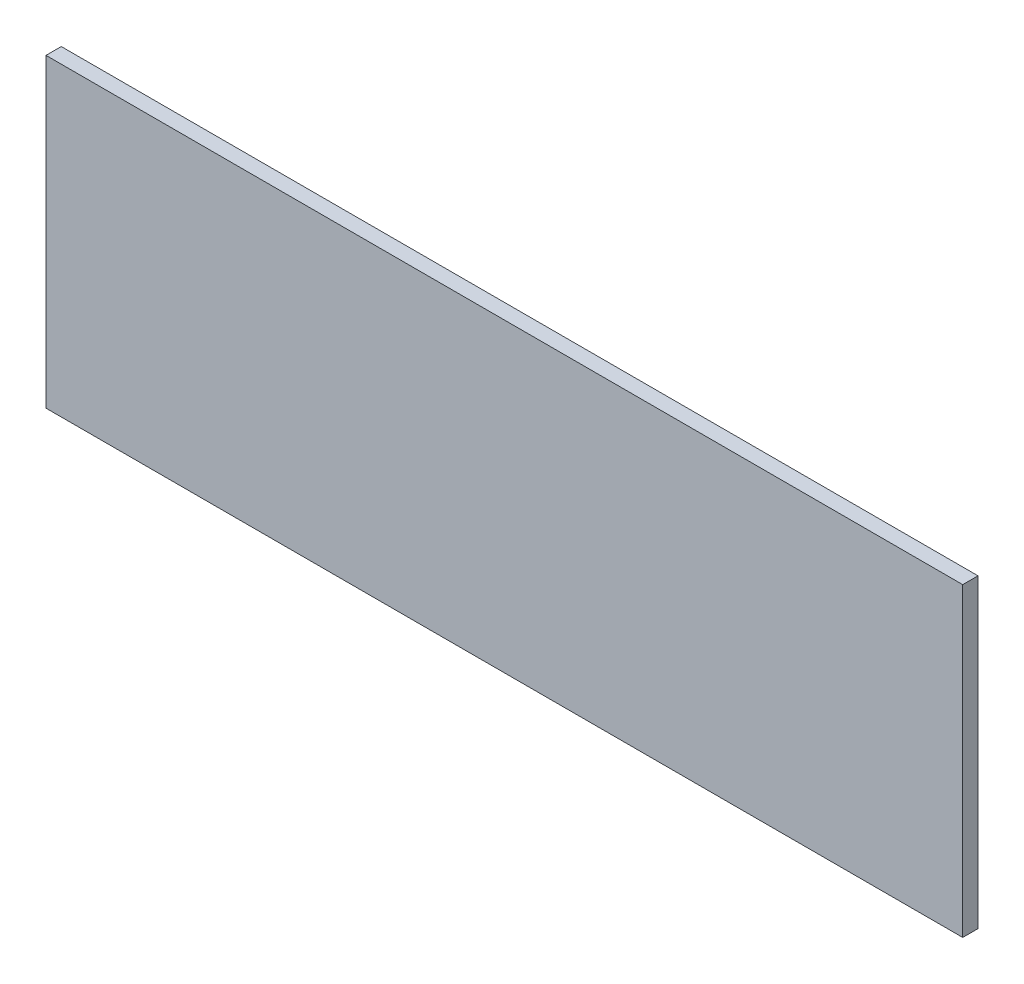
SolidWorks part; units mm, degrees
ref_plane "Front Plane" through (0, 0, 0) normal (0, 0, 1) x (1, 0, 0)
ref_plane "Top Plane" through (0, 0, 0) normal (0, 1, 0) x (1, 0, 0)
ref_plane "Right Plane" through (0, 0, 0) normal (1, 0, 0) x (0, 0, -1)
sketch "Sketch1" plane through (0, 0, 0) normal (0, 0, 1) x (1, 0, 0)
  line L1 (-200, 100) -> (200, 100)
  line L2 (-200, 100) -> (-200, -100)
  line L3 (-200, -100) -> (200, -100)
  line L5 (-200, 100) -> (200, -100) construction
  line L6 (-200, -100) -> (200, 100) construction
  line L7 (200, 100) -> (400, 100)
  line L8 (200, -100) -> (400, -100)
  line L9 (400, 100) -> (400, -100)
  point P0 (0, 0)
  dimension "D1" = 200
  dimension "D2" = 400
  dimension "D3" = 200
extrude "Boss-Extrude1" add sketch "Sketch1" along normal blind 10
sketch "Sketch3" plane through (0, 0, 0) normal (0, 0, -1) x (-1, 0, 0)
  spline S0 degree 3 poles (-2103.044, -412.5967) (-138.6618, 39.5877) (-149.3356, 4.7915) (-141.5972, -25.7549) (-141.3851, -26.5649) (-140.9483, -28.1756) (-140.2446, -30.5661) (-139.1948, -33.7177) (-138.0374, -36.8155) (-136.7647, -39.8695) (-135.3768, -42.8702) (-133.3544, -46.8191) (-131.077, -50.6438) (-128.5469, -54.3011) (-125.8557, -57.822) (-122.1581, -61.9709) (-118.0039, -65.6803) (-114.4131, -68.3205) (-111.5974, -70.117) (-108.6603, -71.7145) (-105.6074, -73.092) (-103.2397, -73.9413) (-101.6398, -74.4242) (-100.5725, -74.7229) (-99.4987, -74.9944) (-98.4217, -75.2497) (-97.6125, -75.4336) (-96.7995, -75.601) (-96.1176, -75.7197) (-95.5687, -75.7973) (-95.0161, -75.8615) (-94.3206, -75.9186) (-93.4815, -75.9596) (-92.3569, -75.9891) (-90.9501, -76.0046) (-88.7075, -75.9914) (-84.8192, -75.8658) (-79.3163, -75.4025) (-72.8072, -74.3996) (-66.4135, -72.9513) (-61.1873, -71.3725) (-57.0748, -69.8846) (-54.016, -68.6584) (-51.4903, -67.5601) (-49.733, -66.7559) (-48.7295, -66.2891) (-47.7259, -65.8211) (-46.4718, -65.238) (-44.9619, -64.5555) (-43.4435, -63.9038) (-41.4062, -63.0949) (-38.8202, -62.2269) (-35.6692, -61.409) (-32.4892, -60.8066) (-29.2864, -60.4114) (-26.0597, -60.227) (-21.7372, -60.2649) (-16.358, -60.8508) (-10.0423, -62.3605) (-4.9801, -64.2578) (-1.0877, -66.1201) (2.6668, -68.1776) (5.7965, -70.2311) (8.3567, -72.1484) (9.6149, -73.1407) (10.8539, -74.1603) (12.08, -75.1985) (13.0957, -76.0723) (13.9077, -76.7724) (14.7203, -77.4717) (15.7387, -78.3412) (18.1964, -80.391) (21.1717, -82.6384) (24.6975, -85.0082) (28.2948, -87.2478) (32.9457, -89.817) (38.7345, -92.4949) (44.6974, -94.7395) (49.7741, -96.2372) (53.8817, -97.2085) (58.0277, -98.0311) (62.2288, -98.6221) (66.4638, -98.9777) (69.6537, -99.1259) (72.3099, -99.1496) (74.4268, -99.1084) (76.0095, -99.0496) (77.5877, -98.9453) (79.1599, -98.7734) (80.7214, -98.5102) (82.014, -98.2345) (83.0455, -97.992) (84.0772, -97.7381) (85.366, -97.4064) (86.9086, -96.9779) (89.968, -96.0479) (94.44, -94.3374) (100.1185, -91.4474) (105.4889, -88.0088) (110.5186, -84.0822) (115.1857, -79.7432) (119.486, -75.0613) (122.7728, -70.8985) (125.2277, -67.4262) (127.5654, -63.8758) (130.2574, -59.3139) (133.1356, -53.6666) (135.6782, -47.8668) (137.901, -41.9212) (139.8079, -35.8493) (141.3941, -29.6865) (143.0896, -21.4114) (144.1744, -13.039) (144.6614, -4.6217) (144.73, 1.7277) (144.4987, 8.0857) (143.966, 14.4203) (143.1325, 20.6999) (142.0013, 26.9163) (140.5653, 33.0686) (138.8133, 39.1546) (137.0814, 44.1587) (135.5305, 48.114) (133.8715, 52.0226) (131.5948, 56.8003) (128.5254, 62.3462) (125.1108, 67.6892) (121.3313, 72.8117) (117.1838, 77.6611) (112.6706, 82.1765) (108.6097, 85.6081) (105.1813, 88.1308) (101.6385, 90.4942) (97.016, 93.1198) (92.1521, 95.2503) (88.6428, 96.4569) (86.6016, 97.0655) (85.0554, 97.4883) (83.502, 97.8836) (81.947, 98.2551) (80.6462, 98.5253) (79.6027, 98.7062) (78.5591, 98.8586) (77.3228, 98.9854) (75.8947, 99.0754) (74.0858, 99.1407) (70.9094, 99.1782) (64.5484, 98.9511) (58.2193, 98.1189) (52.8891, 96.9814) (49.3661, 96.1144) (43.2686, 94.3063) (36.5238, 91.5907) (30.098, 88.2837) (25.4674, 85.5417) (21.7534, 83.0362) (19.2389, 81.1619) (17.8253, 80.054) (16.7768, 79.2037) (15.7398, 78.3362) (14.71, 77.4575) (13.6841, 76.573) (12.6585, 75.688) (11.6298, 74.8077) (10.5945, 73.9375) (9.5494, 73.0823) (7.4405, 71.4187) (4.1612, 69.0971) (-0.7074, 66.2441) (-6.1007, 63.7545) (-11.0366, 62.1303) (-15.073, 61.1986) (-19.151, 60.5108) (-23.3802, 60.1921) (-27.7041, 60.2908) (-31.0555, 60.6008) (-34.3579, 61.135) (-37.5971, 61.8847) (-40.2416, 62.6944) (-42.3186, 63.4571) (-43.8608, 64.0843) (-45.3907, 64.7516) (-46.6583, 65.3299) (-47.6708, 65.7991) (-48.4301, 66.1527) (-49.1895, 66.5058) (-50.7076, 67.2071) (-52.9946, 68.2257) (-56.0728, 69.4956) (-59.178, 70.6598) (-63.3494, 72.053) (-68.639, 73.5101) (-75.0953, 74.805) (-81.6477, 75.6514) (-87.1601, 75.9791) (-90.7557, 76.0061) (-92.4126, 75.9822) (-93.2401, 75.9639) (-94.067, 75.9336) (-94.8931, 75.8806) (-95.7178, 75.7946) (-96.5394, 75.6641) (-97.3583, 75.5007) (-98.1756, 75.3152) (-98.9922, 75.1188) (-99.8081, 74.9172) (-100.6208, 74.7063) (-101.7737, 74.3888) (-103.1036, 73.9754) (-105.1979, 73.23) (-107.6898, 72.1814) (-110.6684, 70.6547) (-113.5314, 68.9174) (-116.2634, 66.9925) (-118.8555, 64.9024) (-121.3161, 62.6603) (-123.6524, 60.2753) (-125.8591, 57.7624) (-127.9232, 55.1474) (-129.8577, 52.4389) (-131.6565, 49.6561) (-133.3379, 46.7834) (-134.6705, 44.2667) (-135.7192, 42.1223) (-136.5215, 40.3817) (-137.2867, 38.6183) (-138.0114, 36.8422) (-138.6959, 35.0563) (-139.3433, 33.2547) (-139.9518, 31.4437) (-140.5219, 29.6262) (-141.0527, 27.8046) (-152.0193, -12.6029) (-130.3539, -60.6852) (-2104.5331, 401.2096) knots -0.118191 -0.118191 -0.118191 -0.118191 0.001078 0.002155 0.00323 0.004304 0.008586 0.01283 0.017102 0.021326 0.025576 0.029838 0.038418 0.042702 0.046969 0.055489 0.064076 0.068373 0.072653 0.076936 0.081245 0.085547 0.086616 0.087684 0.089817 0.090883 0.091949 0.093015 0.094081 0.094615 0.095151 0.096225 0.097304 0.098387 0.10056 0.102725 0.107029 0.115547 0.123986 0.132386 0.140788 0.145004 0.149235 0.153484 0.155615 0.156682 0.157749 0.159882 0.162011 0.164134 0.166249 0.170457 0.174635 0.178783 0.182919 0.187062 0.191228 0.199566 0.207847 0.216188 0.220342 0.224467 0.232679 0.234734 0.236792 0.238853 0.240917 0.242983 0.244016 0.245049 0.247113 0.249176 0.25738 0.261464 0.265543 0.273705 0.28192 0.290099 0.298235 0.302296 0.306361 0.314519 0.318626 0.322734 0.326821 0.328858 0.330893 0.332923 0.334952 0.336984 0.339022 0.340044 0.341067 0.343116 0.345172 0.347236 0.355437 0.363579 0.371748 0.379971 0.388134 0.396275 0.404444 0.408552 0.412659 0.420821 0.428948 0.437069 0.44521 0.453395 0.461581 0.46972 0.485934 0.494052 0.5022 0.510392 0.518559 0.526686 0.534792 0.542897 0.55102 0.559185 0.563291 0.567389 0.575545 0.583671 0.591798 0.599962 0.608181 0.616363 0.624536 0.62864 0.63276 0.640942 0.649089 0.65318 0.655235 0.657296 0.659357 0.661411 0.663456 0.664475 0.665491 0.667519 0.669261 0.671004 0.674494 0.6815 0.695518 0.699009 0.7025 0.709496 0.723503 0.730431 0.737331 0.744227 0.747683 0.749414 0.751148 0.752884 0.754623 0.756364 0.758104 0.759843 0.761581 0.763315 0.765047 0.771931 0.778777 0.786765 0.794774 0.798749 0.802719 0.810703 0.815041 0.819374 0.823661 0.827922 0.832176 0.834308 0.836446 0.83859 0.840739 0.841815 0.842891 0.843967 0.845042 0.849335 0.853613 0.857871 0.862111 0.870556 0.878993 0.887464 0.895994 0.900253 0.901317 0.90238 0.903443 0.904505 0.905569 0.906637 0.907709 0.908786 0.909866 0.910946 0.912024 0.913101 0.915554 0.917388 0.921666 0.92596 0.930274 0.93456 0.938828 0.943097 0.94738 0.951686 0.955977 0.960212 0.964507 0.96874 0.973034 0.975477 0.977938 0.980419 0.982884 0.985329 0.987788 0.99026 0.99269 0.995127 0.997571 1.15401 1.15401 1.15401 1.15401 only from (-142.0003, -24.1267) to (-142.0003, 24.133) construction
  spline S1 degree 3 poles (-142.0003, -24.1267) (-141.9345, -24.3987) (-141.803, -24.9423) (-141.5972, -25.7549) (-141.3851, -26.5649) (-140.9483, -28.1756) (-140.2446, -30.5661) (-139.1948, -33.7177) (-138.0374, -36.8155) (-136.7647, -39.8695) (-135.3768, -42.8702) (-133.3544, -46.8191) (-131.077, -50.6438) (-128.5469, -54.3011) (-125.8557, -57.822) (-122.1581, -61.9709) (-118.0039, -65.6803) (-114.4131, -68.3205) (-111.5974, -70.117) (-108.6603, -71.7145) (-105.6074, -73.092) (-103.2397, -73.9413) (-101.6398, -74.4242) (-100.5725, -74.7229) (-99.4987, -74.9944) (-98.4217, -75.2497) (-97.6125, -75.4336) (-96.7995, -75.601) (-96.1176, -75.7197) (-95.5687, -75.7973) (-95.0161, -75.8615) (-94.3206, -75.9186) (-93.4815, -75.9596) (-92.3569, -75.9891) (-90.9501, -76.0046) (-88.7075, -75.9914) (-84.8192, -75.8658) (-79.3163, -75.4025) (-72.8072, -74.3996) (-66.4135, -72.9513) (-61.1873, -71.3725) (-57.0748, -69.8846) (-54.016, -68.6584) (-51.4903, -67.5601) (-49.733, -66.7559) (-48.7295, -66.2891) (-47.7259, -65.8211) (-46.4718, -65.238) (-44.9619, -64.5555) (-43.4435, -63.9038) (-41.4062, -63.0949) (-38.8202, -62.2269) (-35.6692, -61.409) (-32.4892, -60.8066) (-29.2864, -60.4114) (-26.0597, -60.227) (-21.7372, -60.2649) (-16.358, -60.8508) (-10.0423, -62.3605) (-4.9801, -64.2578) (-1.0877, -66.1201) (2.6668, -68.1776) (5.7965, -70.2311) (8.3567, -72.1484) (9.6149, -73.1407) (10.8539, -74.1603) (12.08, -75.1985) (13.0957, -76.0723) (13.9077, -76.7724) (14.7203, -77.4717) (15.7387, -78.3412) (18.1964, -80.391) (21.1717, -82.6384) (24.6975, -85.0082) (28.2948, -87.2478) (32.9457, -89.817) (38.7345, -92.4949) (44.6974, -94.7395) (49.7741, -96.2372) (53.8817, -97.2085) (58.0277, -98.0311) (62.2288, -98.6221) (66.4638, -98.9777) (69.6537, -99.1259) (72.3099, -99.1496) (74.4268, -99.1084) (76.0095, -99.0496) (77.5877, -98.9453) (79.1599, -98.7734) (80.7214, -98.5102) (82.014, -98.2345) (83.0455, -97.992) (84.0772, -97.7381) (85.366, -97.4064) (86.9086, -96.9779) (89.968, -96.0479) (94.44, -94.3374) (100.1185, -91.4474) (105.4889, -88.0088) (110.5186, -84.0822) (115.1857, -79.7432) (119.486, -75.0613) (122.7728, -70.8985) (125.2277, -67.4262) (127.5654, -63.8758) (130.2574, -59.3139) (133.1356, -53.6666) (135.6782, -47.8668) (137.901, -41.9212) (139.8079, -35.8493) (141.3941, -29.6865) (143.0896, -21.4114) (144.1744, -13.039) (144.6614, -4.6217) (144.73, 1.7277) (144.4987, 8.0857) (143.966, 14.4203) (143.1325, 20.6999) (142.0013, 26.9163) (140.5653, 33.0686) (138.8133, 39.1546) (137.0814, 44.1587) (135.5305, 48.114) (133.8715, 52.0226) (131.5948, 56.8003) (128.5254, 62.3462) (125.1108, 67.6892) (121.3313, 72.8117) (117.1838, 77.6611) (112.6706, 82.1765) (108.6097, 85.6081) (105.1813, 88.1308) (101.6385, 90.4942) (97.016, 93.1198) (92.1521, 95.2503) (88.6428, 96.4569) (86.6016, 97.0655) (85.0554, 97.4883) (83.502, 97.8836) (81.947, 98.2551) (80.6462, 98.5253) (79.6027, 98.7062) (78.5591, 98.8586) (77.3228, 98.9854) (75.8947, 99.0754) (74.0858, 99.1407) (70.9094, 99.1782) (64.5484, 98.9511) (58.2193, 98.1189) (52.8891, 96.9814) (49.3661, 96.1144) (43.2686, 94.3063) (36.5238, 91.5907) (30.098, 88.2837) (25.4674, 85.5417) (21.7534, 83.0362) (19.2389, 81.1619) (17.8253, 80.054) (16.7768, 79.2037) (15.7398, 78.3362) (14.71, 77.4575) (13.6841, 76.573) (12.6585, 75.688) (11.6298, 74.8077) (10.5945, 73.9375) (9.5494, 73.0823) (7.4405, 71.4187) (4.1612, 69.0971) (-0.7074, 66.2441) (-6.1007, 63.7545) (-11.0366, 62.1303) (-15.073, 61.1986) (-19.151, 60.5108) (-23.3802, 60.1921) (-27.7041, 60.2908) (-31.0555, 60.6008) (-34.3579, 61.135) (-37.5971, 61.8847) (-40.2416, 62.6944) (-42.3186, 63.4571) (-43.8608, 64.0843) (-45.3907, 64.7516) (-46.6583, 65.3299) (-47.6708, 65.7991) (-48.4301, 66.1527) (-49.1895, 66.5058) (-50.7076, 67.2071) (-52.9946, 68.2257) (-56.0728, 69.4956) (-59.178, 70.6598) (-63.3494, 72.053) (-68.639, 73.5101) (-75.0953, 74.805) (-81.6477, 75.6514) (-87.1601, 75.9791) (-90.7557, 76.0061) (-92.4126, 75.9822) (-93.2401, 75.9639) (-94.067, 75.9336) (-94.8931, 75.8806) (-95.7178, 75.7946) (-96.5394, 75.6641) (-97.3583, 75.5007) (-98.1756, 75.3152) (-98.9922, 75.1188) (-99.8081, 74.9172) (-100.6208, 74.7063) (-101.7737, 74.3888) (-103.1036, 73.9754) (-105.1979, 73.23) (-107.6898, 72.1814) (-110.6684, 70.6547) (-113.5314, 68.9174) (-116.2634, 66.9925) (-118.8555, 64.9024) (-121.3161, 62.6603) (-123.6524, 60.2753) (-125.8591, 57.7624) (-127.9232, 55.1474) (-129.8577, 52.4389) (-131.6565, 49.6561) (-133.3379, 46.7834) (-134.6705, 44.2667) (-135.7192, 42.1223) (-136.5215, 40.3817) (-137.2867, 38.6183) (-138.0114, 36.8422) (-138.6959, 35.0563) (-139.3433, 33.2547) (-139.9518, 31.4437) (-140.5219, 29.6262) (-141.0527, 27.8046) (-141.5496, 25.9737) (-141.8504, 24.7453) (-142.0003, 24.133) knots 0 0 0 0 0.001078 0.002155 0.00323 0.004304 0.008586 0.01283 0.017102 0.021326 0.025576 0.029838 0.038418 0.042702 0.046969 0.055489 0.064076 0.068373 0.072653 0.076936 0.081245 0.085547 0.086616 0.087684 0.089817 0.090883 0.091949 0.093015 0.094081 0.094615 0.095151 0.096225 0.097304 0.098387 0.10056 0.102725 0.107029 0.115547 0.123986 0.132386 0.140788 0.145004 0.149235 0.153484 0.155615 0.156682 0.157749 0.159882 0.162011 0.164134 0.166249 0.170457 0.174635 0.178783 0.182919 0.187062 0.191228 0.199566 0.207847 0.216188 0.220342 0.224467 0.232679 0.234734 0.236792 0.238853 0.240917 0.242983 0.244016 0.245049 0.247113 0.249176 0.25738 0.261464 0.265543 0.273705 0.28192 0.290099 0.298235 0.302296 0.306361 0.314519 0.318626 0.322734 0.326821 0.328858 0.330893 0.332923 0.334952 0.336984 0.339022 0.340044 0.341067 0.343116 0.345172 0.347236 0.355437 0.363579 0.371748 0.379971 0.388134 0.396275 0.404444 0.408552 0.412659 0.420821 0.428948 0.437069 0.44521 0.453395 0.461581 0.46972 0.485934 0.494052 0.5022 0.510392 0.518559 0.526686 0.534792 0.542897 0.55102 0.559185 0.563291 0.567389 0.575545 0.583671 0.591798 0.599962 0.608181 0.616363 0.624536 0.62864 0.63276 0.640942 0.649089 0.65318 0.655235 0.657296 0.659357 0.661411 0.663456 0.664475 0.665491 0.667519 0.669261 0.671004 0.674494 0.6815 0.695518 0.699009 0.7025 0.709496 0.723503 0.730431 0.737331 0.744227 0.747683 0.749414 0.751148 0.752884 0.754623 0.756364 0.758104 0.759843 0.761581 0.763315 0.765047 0.771931 0.778777 0.786765 0.794774 0.798749 0.802719 0.810703 0.815041 0.819374 0.823661 0.827922 0.832176 0.834308 0.836446 0.83859 0.840739 0.841815 0.842891 0.843967 0.845042 0.849335 0.853613 0.857871 0.862111 0.870556 0.878993 0.887464 0.895994 0.900253 0.901317 0.90238 0.903443 0.904505 0.905569 0.906637 0.907709 0.908786 0.909866 0.910946 0.912024 0.913101 0.915554 0.917388 0.921666 0.92596 0.930274 0.93456 0.938828 0.943097 0.94738 0.951686 0.955977 0.960212 0.964507 0.96874 0.973034 0.975477 0.977938 0.980419 0.982884 0.985329 0.987788 0.99026 0.99269 0.995127 0.997571 1 1 1 1
